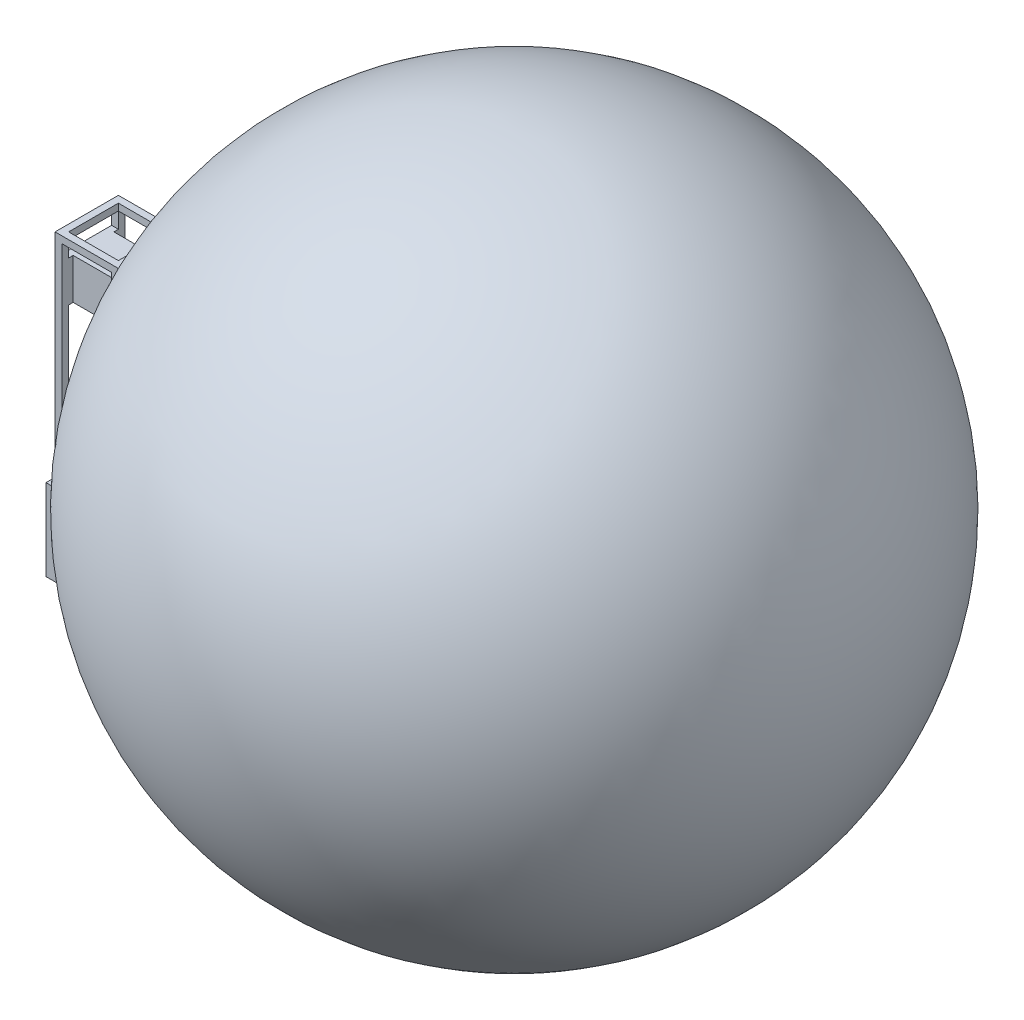
SolidWorks part; units mm, degrees
ref_plane "Front Plane" through (0, 0, 0) normal (0, 0, 1) x (1, 0, 0)
ref_plane "Top Plane" through (0, 0, 0) normal (0, 1, 0) x (1, 0, 0)
ref_plane "Right Plane" through (0, 0, 0) normal (1, 0, 0) x (0, 0, -1)
sketch "Sketch1" plane through (0, 0, 0) normal (0, 1, 0) x (1, 0, 0)
  line L1 (0, 0) -> (640, 0)
  line L2 (0, 0) -> (0, 160)
  line L3 (0, 160) -> (640, 160)
  line L4 (640, 0) -> (640, 160)
  dimension "D1" = 160
  dimension "D2" = 640
extrude "Boss-Extrude1" add sketch "Sketch1" along normal blind 180
sketch "Sketch2" plane through (640, 0, 0) normal (1, 0, 0) x (0, 0, -1)
  line L0 (160, 180) -> (160, 0) construction
  line L1 (0, 180) -> (160, 180)
  line L2 (0, 180) -> (0, 20)
  line L3 (0, 20) -> (160, 20)
  line L4 (160, 180) -> (160, 20)
  dimension "D1" = 160
extrude "Cut-Extrude1" cut sketch "Sketch2" against normal blind 480
sketch "Sketch3" plane through (160, 0, 0) normal (1, 0, 0) x (0, 0, -1)
  line L0 (0, 100) -> (160, 100) construction
  line L1 (0, 180) -> (0, 20) construction
  line L2 (160, 20) -> (160, 180) construction
  circle A0 centre (80, 100) radius 70
  dimension "D1" = 140
ref_plane "Plane1" through (0, 0, -80) normal (0, 0, 1) x (1, 0, 0)
ref_plane "Plane2" through (0, 100, 0) normal (0, 1, 0) x (1, 0, 0)
sketch "Sketch4" plane through (160, 0, 0) normal (1, 0, 0) x (0, 0, -1)
  line L0 (0, 180) -> (10, 180) construction
  line L1 (160, 180) -> (0, 180) construction
  line L2 (0, 180) -> (0, 170) construction
  line L3 (0, 180) -> (0, 20) construction
  line L4 (0, 170) -> (10, 170) construction
  line L5 (10, 170) -> (10, 180) construction
  line L6 (80, 180) -> (80, 20) construction
  line L7 (10, 170) -> (25, 170)
  line L8 (10, 170) -> (10, 155)
  line L9 (10, 155) -> (25, 155)
  line L10 (25, 170) -> (25, 155)
  line L11 (0, 20) -> (160, 20) construction
  line L12 (0, 100) -> (160, 100) construction
  line L13 (160, 20) -> (160, 180) construction
  line L14 (150, 155) -> (135, 155)
  line L15 (135, 170) -> (135, 155)
  line L16 (150, 170) -> (135, 170)
  line L17 (150, 170) -> (150, 155)
  line L18 (150, 30) -> (150, 45)
  line L19 (150, 30) -> (135, 30)
  line L20 (135, 30) -> (135, 45)
  line L21 (150, 45) -> (135, 45)
  line L22 (10, 45) -> (25, 45)
  line L23 (25, 30) -> (25, 45)
  line L24 (10, 30) -> (25, 30)
  line L25 (10, 30) -> (10, 45)
  dimension "D1" = 10
  dimension "D2" = 15
sketch "Sketch5" plane through (0, 180, 0) normal (0, 1, 0) x (1, 0, 0)
  line L0 (0, 160) -> (10, 160) construction
  line L1 (160, 160) -> (0, 160) construction
  line L2 (0, 160) -> (0, 150) construction
  line L3 (0, 160) -> (0, 0) construction
  line L4 (0, 150) -> (10, 150) construction
  line L5 (10, 150) -> (10, 160) construction
  line L6 (80, 160) -> (80, 0) construction
  line L7 (10, 150) -> (25, 150)
  line L8 (10, 150) -> (10, 135)
  line L9 (10, 135) -> (25, 135)
  line L10 (25, 150) -> (25, 135)
  line L11 (0, 0) -> (160, 0) construction
  line L12 (0, 80) -> (160, 80) construction
  line L13 (160, 0) -> (160, 160) construction
  line L14 (150, 135) -> (135, 135)
  line L15 (135, 150) -> (135, 135)
  line L16 (150, 150) -> (135, 150)
  line L17 (150, 150) -> (150, 135)
  line L18 (150, 10) -> (150, 25)
  line L19 (150, 10) -> (135, 10)
  line L20 (135, 10) -> (135, 25)
  line L21 (150, 25) -> (135, 25)
  line L22 (10, 25) -> (25, 25)
  line L23 (25, 10) -> (25, 25)
  line L24 (10, 10) -> (25, 10)
  line L25 (10, 10) -> (10, 25)
  dimension "D1" = 10
  dimension "D2" = 15
extrude "Boss-Extrude2" add sketch "Sketch5" along normal blind 480
sketch "Sketch6" plane through (25, 0, 0) normal (1, 0, 0) x (0, 0, -1)
  line L0 (25, 660) -> (25, 180) construction
  line L1 (10, 660) -> (25, 660)
  line L2 (10, 660) -> (10, 645)
  line L3 (10, 645) -> (25, 645)
  line L4 (25, 660) -> (25, 645)
  line L5 (150, 660) -> (150, 180) construction
  line L6 (135, 660) -> (150, 660)
  line L7 (135, 660) -> (135, 645)
  line L8 (135, 645) -> (150, 645)
  line L9 (150, 660) -> (150, 645)
  dimension "D1" = 15
extrude "Boss-Extrude3" add sketch "Sketch6" along normal up to surface (110 mm away) up to face at (135, 420, -17.5)
sketch "Sketch7" plane through (0, 0, -25) normal (0, 0, -1) x (-1, 0, 0)
  line L1 (-150, 660) -> (-135, 660)
  line L2 (-150, 660) -> (-150, 645)
  line L3 (-150, 645) -> (-135, 645)
  line L4 (-135, 660) -> (-135, 645)
  line L5 (-25, 645) -> (-10, 645)
  line L6 (-25, 645) -> (-25, 660)
  line L7 (-25, 660) -> (-10, 660)
  line L8 (-10, 645) -> (-10, 660)
extrude "Boss-Extrude4" add sketch "Sketch7" along normal up to surface (110 mm away) up to face at (80, 416.25, -135)
sketch "Sketch9" plane through (150, 0, 0) normal (1, 0, 0) x (0, 0, -1)
  line L0 (135, 645) -> (25, 645) construction
  line L2 (25, 645) -> (25, 180) construction
  line L3 (35, 520) -> (125, 520)
  line L4 (35, 520) -> (35, 610)
  line L5 (35, 610) -> (125, 610)
  line L6 (125, 520) -> (125, 610)
  line L7 (35, 520) -> (125, 610) construction
  line L8 (35, 610) -> (125, 520) construction
  point P4 (80, 565)
  dimension "D1" = 80
  dimension "D2" = 10
  dimension "D3" = 90
extrude "Boss-Extrude5" add sketch "Sketch9" against normal up to surface (140 mm away) separate body up to face at (10, 416.25, -80)
sketch "Sketch10" plane through (0, 0, -35) normal (0, 0, 1) x (1, 0, 0)
  line L0 (10, 520) -> (150, 520) construction
  line L1 (10, 610) -> (25, 610)
  line L2 (10, 610) -> (10, 520)
  line L3 (10, 520) -> (25, 520)
  line L4 (25, 610) -> (25, 520)
  line L5 (25, 645) -> (25, 180) construction
  line L6 (135, 645) -> (135, 180) construction
  line L7 (150, 610) -> (135, 610)
  line L8 (150, 610) -> (150, 520)
  line L9 (150, 520) -> (135, 520)
  line L10 (135, 610) -> (135, 520)
extrude "Boss-Extrude6" add sketch "Sketch10" along normal up to surface and the other way up to surface up to face at (17.5, 412.5, -25) other way up to face at (17.5, 412.5, -135)
sketch "Sketch8" plane through (150, 0, 0) normal (1, 0, 0) x (0, 0, -1)
  line L0 (80, 645) -> (80, 635) construction
  line L1 (135, 645) -> (25, 645) construction
  line L2 (80, 565) -> (80, 635) construction
  circle A0 centre (80, 565) radius 70
  dimension "D2" = 140
  dimension "D1" = 10
extrude "Boss-Extrude7" add sketch "Sketch8" along normal blind 80
sketch "Sketch11" plane through (0, 0, -80) normal (0, 0, 1) x (1, 0, 0)
  line L0 (150, 565) -> (640, 565) construction
  line L1 (640, 20) -> (640, 565) construction
  line L2 (230, 495) -> (230, 635) construction
  line L3 (430, 65) -> (430, 1065) construction
  line L4 (955, 1290) -> (955, -160)
  arc A0 (955, 1290) -> (955, -160) centre (955, 565) ccw
  point P13 (430, 565)
  dimension "D1" = 200
  dimension "D2" = 1000
revolve "Revolve1" add sketch "Sketch11" angle 360 about L4
sketch "Sketch12" plane through (0, 0, -80) normal (0, 0, 1) x (1, 0, 0)
  line L0 (230, 565) -> (430, 565) construction
  line L1 (230, 495) -> (230, 635) construction
  line L2 (430, -235) -> (430, 1365)
  line L3 (430, 1365) -> (2030, 1365)
  line L4 (2030, 1365) -> (2030, -235)
  line L5 (2030, -235) -> (430, -235)
  point P7 (430, 565)
  dimension "D1" = 200
  dimension "D2" = 1600
